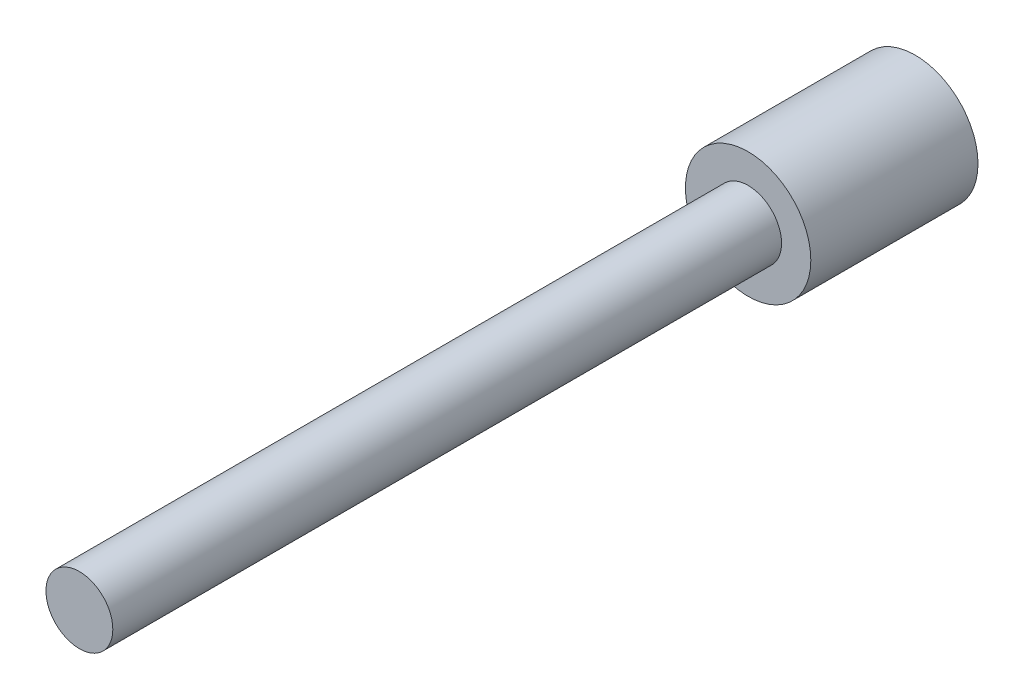
SolidWorks part; units mm, degrees
ref_plane "Plano frontal" through (0, 0, 0) normal (0, 0, 1) x (1, 0, 0)
ref_plane "Plano superior" through (0, 0, 0) normal (0, 1, 0) x (1, 0, 0)
ref_plane "Plano direito" through (0, 0, 0) normal (1, 0, 0) x (0, 0, -1)
sketch "Esboço1" plane through (0, 0, 0) normal (0, 0, 1) x (1, 0, 0)
  circle A0 centre (0, 0) radius 7.5
  dimension "D1" = 15
extrude "Ressalto-extrusão1" add sketch "Esboço1" along normal blind 20
sketch "Esboço2" plane through (0, 0, 20) normal (0, 0, 1) x (1, 0, 0)
  circle A0 centre (0, 0) radius 4
  dimension "D1" = 8
extrude "Ressalto-extrusão2" add sketch "Esboço2" along normal blind 80
